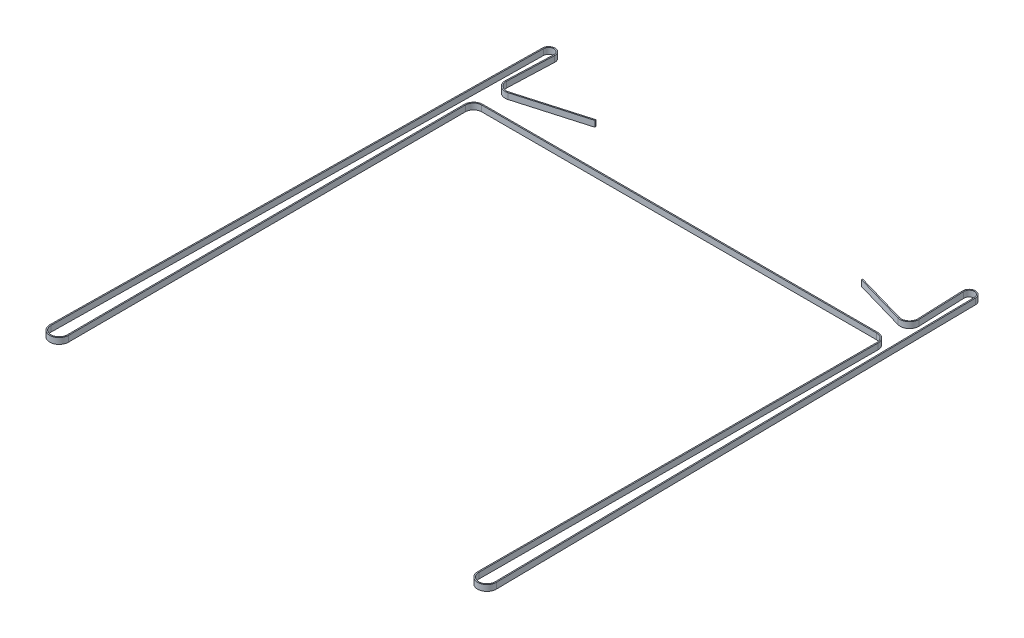
SolidWorks part; units mm, degrees
ref_plane "Front Plane" through (0, 0, 0) normal (0, 0, 1) x (1, 0, 0)
ref_plane "Top Plane" through (0, 0, 0) normal (0, 1, 0) x (1, 0, 0)
ref_plane "Right Plane" through (0, 0, 0) normal (1, 0, 0) x (0, 0, -1)
ref_plane "Plane1" through (0, 98.1376, 0) normal (0, 1, 0) x (1, 0, 0)
sketch "Sketch1" plane through (0, 0, 0) normal (0, 1, 0) x (1, 0, 0)
  line L0 (476.8725, -41.4029) -> (484.0321, -561.6139)
  line L1 (466.5329, -561.7109) -> (467.6763, -135.5617)
  line L2 (465.7551, -41.6937) -> (467.669, -91.3316)
  line L3 (457.7263, -125.585) -> (217.9548, -125.585)
  line L4 (37.4885, -101.276) -> (109.817, -80.4354)
  line L5 (246.23, -12.3063) -> (246.23, 12.3063) construction
  line L6 (246.23, -327.9877) -> (246.23, -29.8379) construction
  line L7 (25.9271, -561.7109) -> (24.7837, -135.5617)
  line L8 (15.5875, -41.4029) -> (8.4279, -561.6139)
  line L9 (26.7049, -41.6937) -> (24.791, -91.3316)
  line L10 (34.7337, -125.585) -> (217.9548, -125.585)
  line L11 (454.9715, -101.276) -> (400.0235, -85.4434)
  circle A1 centre (475.2829, -561.7344) radius 8.75 construction
  circle A2 centre (457.7263, -135.535) radius 8.75 construction
  circle A3 centre (457.7263, -135.535) radius 8.75 construction
  circle A4 centre (475.2829, -561.7344) radius 8.75
  circle A5 centre (457.7263, -91.715) radius 8.75 construction
  arc A6 (466.6098, -44.3778) -> (467.5641, -45.5151) centre (471.31, -41.4029) ccw construction
  circle A7 centre (471.31, -41.4029) radius 5.5625 construction
  arc A8 (484.0321, -561.6139) -> (466.5329, -561.7109) centre (475.2829, -561.7344) cw
  arc A9 (467.6763, -135.5617) -> (457.7263, -125.585) centre (457.7263, -135.535) ccw
  arc A10 (476.8725, -41.4029) -> (465.7551, -41.6937) centre (471.312, -41.4794) ccw
  arc A11 (467.669, -91.3316) -> (454.9715, -101.276) centre (457.7263, -91.715) cw
  circle A14 centre (34.7337, -135.535) radius 9.95 construction
  arc A15 (8.4279, -561.6139) -> (25.9271, -561.7109) centre (17.1771, -561.7344) ccw
  arc A16 (15.5875, -41.4029) -> (26.7049, -41.6937) centre (21.148, -41.4794) cw
  arc A17 (24.791, -91.3316) -> (37.4885, -101.276) centre (34.7337, -91.715) ccw
  arc A18 (24.7837, -135.5617) -> (34.7337, -125.585) centre (34.7337, -135.535) cw
  circle A19 centre (471.31, -41.4029) radius 8 construction
  circle A20 centre (471.31, -41.4029) radius 8
  circle A21 centre (471.31, -41.4029) radius 8 construction
  circle A22 centre (471.31, -41.4029) radius 8
  circle A23 centre (457.7263, -91.715) radius 8.75 construction
  dimension "D2" = 1.2
  dimension "D1" = 1.2
  dimension "D3" = 0
extrude "Extrude-Thin1" add sketch "Sketch1" along normal blind 6.35 from surface at 98.1376 thin contours A11 L2 A10 L0 A8 L1 A9 L3 starting at plane "Plane1" thin type one direction reverse wall 1.2
